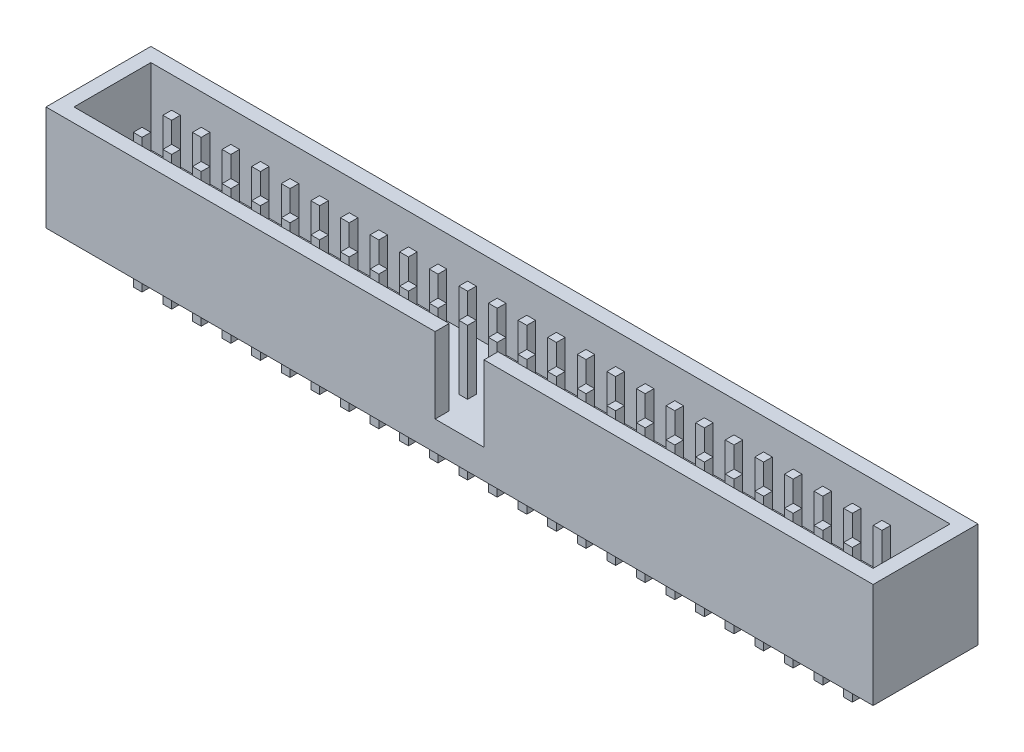
SolidWorks part; units mm, degrees
ref_plane "前视基准面" through (0, 0, 0) normal (0, 0, 1) x (1, 0, 0)
ref_plane "上视基准面" through (0, 0, 0) normal (0, 1, 0) x (1, 0, 0)
ref_plane "右视基准面" through (0, 0, 0) normal (1, 0, 0) x (0, 0, -1)
sketch "草图1" plane through (0, 0, 0) normal (0, 1, 0) x (1, 0, 0)
  line L0 (0, 85.0964) -> (0, -118.2031) construction
  line L1 (-35.49, 4.5) -> (35.49, 4.5)
  line L2 (-35.49, 4.5) -> (-35.49, -4.5)
  line L3 (-35.49, -4.5) -> (35.49, -4.5)
  line L4 (35.49, 4.5) -> (35.49, -4.5)
  line L5 (-200.5452, 0) -> (261.2352, 0) construction
  dimension "D1" = 9
  dimension "D2" = 70.98
extrude "拉伸1" add sketch "草图1" along normal blind 9
sketch "草图2" plane through (0, 9, 0) normal (0, 1, 0) x (-1, 0, 0)
  line L8 (-34.29, 3.3) -> (-34.29, -3.3)
  line L9 (34.29, 3.3) -> (-34.29, 3.3)
  line L10 (34.29, -3.3) -> (34.29, 3.3)
  line L11 (-34.29, -3.3) -> (34.29, -3.3)
  line L12 (-34.29, 3.3) -> (-34.29, -3.3)
  line L13 (34.29, 3.3) -> (-34.29, 3.3)
  line L14 (34.29, -3.3) -> (34.29, 3.3)
  line L15 (-34.29, -3.3) -> (34.29, -3.3)
  dimension "D1" = 1.2
extrude "切除-拉伸1" cut sketch "草图2" against normal blind 6.5
sketch "草图3" plane through (0, 0, 4.5) normal (0, 0, 1) x (1, 0, 0)
  line L0 (-35.49, 9) -> (35.49, 9) construction
  line L1 (-2.1, 9) -> (2.1, 9)
  line L2 (-2.1, 9) -> (-2.1, 2.5)
  line L3 (-2.1, 2.5) -> (2.1, 2.5)
  line L4 (2.1, 9) -> (2.1, 2.5)
  line L5 (-34.29, 2.5) -> (34.29, 2.5) construction
  line L6 (0, 9.4226) -> (0, -4.0288) construction
  dimension "D1" = 4.2
extrude "切除-拉伸2" cut sketch "草图3" against normal blind 6.5
sketch "草图6" plane through (0, 0, 0) normal (0, -1, 0) x (1, 0, 0)
  line L1 (2.1, 3.3) -> (34.29, 3.3) construction
  line L17 (30.85, 1.64) -> (30.1, 1.64)
  line L18 (30.1, 1.64) -> (30.1, 0.89)
  line L19 (30.1, 0.89) -> (30.85, 0.89)
  line L20 (30.85, 0.89) -> (30.85, 1.64)
  line L21 (34.29, 3.3) -> (34.29, -3.3) construction
  line L29 (28.31, 1.64) -> (27.56, 1.64)
  line L30 (27.56, 1.64) -> (27.56, 0.89)
  line L31 (27.56, 0.89) -> (28.31, 0.89)
  line L32 (28.31, 0.89) -> (28.31, 1.64)
  line L33 (25.77, 1.64) -> (25.02, 1.64)
  line L34 (25.02, 1.64) -> (25.02, 0.89)
  line L35 (25.02, 0.89) -> (25.77, 0.89)
  line L36 (25.77, 0.89) -> (25.77, 1.64)
  line L37 (23.23, 1.64) -> (22.48, 1.64)
  line L38 (22.48, 1.64) -> (22.48, 0.89)
  line L39 (22.48, 0.89) -> (23.23, 0.89)
  line L40 (23.23, 0.89) -> (23.23, 1.64)
  line L41 (20.69, 1.64) -> (19.94, 1.64)
  line L42 (19.94, 1.64) -> (19.94, 0.89)
  line L43 (19.94, 0.89) -> (20.69, 0.89)
  line L44 (20.69, 0.89) -> (20.69, 1.64)
  line L45 (18.15, 1.64) -> (17.4, 1.64)
  line L46 (17.4, 1.64) -> (17.4, 0.89)
  line L47 (17.4, 0.89) -> (18.15, 0.89)
  line L48 (18.15, 0.89) -> (18.15, 1.64)
  line L49 (15.61, 1.64) -> (14.86, 1.64)
  line L50 (14.86, 1.64) -> (14.86, 0.89)
  line L51 (14.86, 0.89) -> (15.61, 0.89)
  line L52 (15.61, 0.89) -> (15.61, 1.64)
  line L53 (13.07, 1.64) -> (12.32, 1.64)
  line L54 (12.32, 1.64) -> (12.32, 0.89)
  line L55 (12.32, 0.89) -> (13.07, 0.89)
  line L56 (13.07, 0.89) -> (13.07, 1.64)
  line L57 (10.53, 1.64) -> (9.78, 1.64)
  line L58 (9.78, 1.64) -> (9.78, 0.89)
  line L59 (9.78, 0.89) -> (10.53, 0.89)
  line L60 (10.53, 0.89) -> (10.53, 1.64)
  line L61 (7.99, 1.64) -> (7.24, 1.64)
  line L62 (7.24, 1.64) -> (7.24, 0.89)
  line L63 (7.24, 0.89) -> (7.99, 0.89)
  line L64 (7.99, 0.89) -> (7.99, 1.64)
  line L65 (5.45, 1.64) -> (4.7, 1.64)
  line L66 (4.7, 1.64) -> (4.7, 0.89)
  line L67 (4.7, 0.89) -> (5.45, 0.89)
  line L68 (5.45, 0.89) -> (5.45, 1.64)
  line L69 (2.91, 1.64) -> (2.16, 1.64)
  line L70 (2.16, 1.64) -> (2.16, 0.89)
  line L71 (2.16, 0.89) -> (2.91, 0.89)
  line L72 (2.91, 0.89) -> (2.91, 1.64)
  line L73 (0.37, 1.64) -> (-0.38, 1.64)
  line L74 (-0.38, 1.64) -> (-0.38, 0.89)
  line L75 (-0.38, 0.89) -> (0.37, 0.89)
  line L76 (0.37, 0.89) -> (0.37, 1.64)
  line L77 (-2.17, 1.64) -> (-2.92, 1.64)
  line L78 (-2.92, 1.64) -> (-2.92, 0.89)
  line L79 (-2.92, 0.89) -> (-2.17, 0.89)
  line L80 (-2.17, 0.89) -> (-2.17, 1.64)
  line L81 (-4.71, 1.64) -> (-5.46, 1.64)
  line L82 (-5.46, 1.64) -> (-5.46, 0.89)
  line L83 (-5.46, 0.89) -> (-4.71, 0.89)
  line L84 (-4.71, 0.89) -> (-4.71, 1.64)
  line L85 (-7.25, 1.64) -> (-8, 1.64)
  line L86 (-8, 1.64) -> (-8, 0.89)
  line L87 (-8, 0.89) -> (-7.25, 0.89)
  line L88 (-7.25, 0.89) -> (-7.25, 1.64)
  line L89 (-9.79, 1.64) -> (-10.54, 1.64)
  line L90 (-10.54, 1.64) -> (-10.54, 0.89)
  line L91 (-10.54, 0.89) -> (-9.79, 0.89)
  line L92 (-9.79, 0.89) -> (-9.79, 1.64)
  line L93 (-12.33, 1.64) -> (-13.08, 1.64)
  line L94 (-13.08, 1.64) -> (-13.08, 0.89)
  line L95 (-13.08, 0.89) -> (-12.33, 0.89)
  line L96 (-12.33, 0.89) -> (-12.33, 1.64)
  line L97 (-14.87, 1.64) -> (-15.62, 1.64)
  line L98 (-15.62, 1.64) -> (-15.62, 0.89)
  line L99 (-15.62, 0.89) -> (-14.87, 0.89)
  line L100 (-14.87, 0.89) -> (-14.87, 1.64)
  line L101 (-17.41, 1.64) -> (-18.16, 1.64)
  line L102 (-18.16, 1.64) -> (-18.16, 0.89)
  line L103 (-18.16, 0.89) -> (-17.41, 0.89)
  line L104 (-17.41, 0.89) -> (-17.41, 1.64)
  line L105 (-19.95, 1.64) -> (-20.7, 1.64)
  line L106 (-20.7, 1.64) -> (-20.7, 0.89)
  line L107 (-20.7, 0.89) -> (-19.95, 0.89)
  line L108 (-19.95, 0.89) -> (-19.95, 1.64)
  line L109 (-22.49, 1.64) -> (-23.24, 1.64)
  line L110 (-23.24, 1.64) -> (-23.24, 0.89)
  line L111 (-23.24, 0.89) -> (-22.49, 0.89)
  line L112 (-22.49, 0.89) -> (-22.49, 1.64)
  line L113 (-25.03, 1.64) -> (-25.78, 1.64)
  line L114 (-25.78, 1.64) -> (-25.78, 0.89)
  line L115 (-25.78, 0.89) -> (-25.03, 0.89)
  line L116 (-25.03, 0.89) -> (-25.03, 1.64)
  line L117 (-27.57, 1.64) -> (-28.32, 1.64)
  line L118 (-28.32, 1.64) -> (-28.32, 0.89)
  line L119 (-28.32, 0.89) -> (-27.57, 0.89)
  line L120 (-27.57, 0.89) -> (-27.57, 1.64)
  line L121 (-30.11, 1.64) -> (-30.86, 1.64)
  line L122 (-30.86, 1.64) -> (-30.86, 0.89)
  line L123 (-30.86, 0.89) -> (-30.11, 0.89)
  line L124 (-30.11, 0.89) -> (-30.11, 1.64)
  line L125 (28.31, -0.9) -> (27.56, -0.9)
  line L126 (27.56, -0.9) -> (27.56, -1.65)
  line L127 (27.56, -1.65) -> (28.31, -1.65)
  line L128 (28.31, -1.65) -> (28.31, -0.9)
  line L129 (25.77, -0.9) -> (25.02, -0.9)
  line L130 (25.02, -0.9) -> (25.02, -1.65)
  line L131 (25.02, -1.65) -> (25.77, -1.65)
  line L132 (25.77, -1.65) -> (25.77, -0.9)
  line L133 (23.23, -0.9) -> (22.48, -0.9)
  line L134 (22.48, -0.9) -> (22.48, -1.65)
  line L135 (22.48, -1.65) -> (23.23, -1.65)
  line L136 (23.23, -1.65) -> (23.23, -0.9)
  line L137 (20.69, -0.9) -> (19.94, -0.9)
  line L138 (19.94, -0.9) -> (19.94, -1.65)
  line L139 (19.94, -1.65) -> (20.69, -1.65)
  line L140 (20.69, -1.65) -> (20.69, -0.9)
  line L141 (18.15, -0.9) -> (17.4, -0.9)
  line L142 (17.4, -0.9) -> (17.4, -1.65)
  line L143 (17.4, -1.65) -> (18.15, -1.65)
  line L144 (18.15, -1.65) -> (18.15, -0.9)
  line L145 (15.61, -0.9) -> (14.86, -0.9)
  line L146 (14.86, -0.9) -> (14.86, -1.65)
  line L147 (14.86, -1.65) -> (15.61, -1.65)
  line L148 (15.61, -1.65) -> (15.61, -0.9)
  line L149 (13.07, -0.9) -> (12.32, -0.9)
  line L150 (12.32, -0.9) -> (12.32, -1.65)
  line L151 (12.32, -1.65) -> (13.07, -1.65)
  line L152 (13.07, -1.65) -> (13.07, -0.9)
  line L153 (10.53, -0.9) -> (9.78, -0.9)
  line L154 (9.78, -0.9) -> (9.78, -1.65)
  line L155 (9.78, -1.65) -> (10.53, -1.65)
  line L156 (10.53, -1.65) -> (10.53, -0.9)
  line L157 (7.99, -0.9) -> (7.24, -0.9)
  line L158 (7.24, -0.9) -> (7.24, -1.65)
  line L159 (7.24, -1.65) -> (7.99, -1.65)
  line L160 (7.99, -1.65) -> (7.99, -0.9)
  line L161 (5.45, -0.9) -> (4.7, -0.9)
  line L162 (4.7, -0.9) -> (4.7, -1.65)
  line L163 (4.7, -1.65) -> (5.45, -1.65)
  line L164 (5.45, -1.65) -> (5.45, -0.9)
  line L165 (2.91, -0.9) -> (2.16, -0.9)
  line L166 (2.16, -0.9) -> (2.16, -1.65)
  line L167 (2.16, -1.65) -> (2.91, -1.65)
  line L168 (2.91, -1.65) -> (2.91, -0.9)
  line L169 (0.37, -0.9) -> (-0.38, -0.9)
  line L170 (-0.38, -0.9) -> (-0.38, -1.65)
  line L171 (-0.38, -1.65) -> (0.37, -1.65)
  line L172 (0.37, -1.65) -> (0.37, -0.9)
  line L173 (-2.17, -0.9) -> (-2.92, -0.9)
  line L174 (-2.92, -0.9) -> (-2.92, -1.65)
  line L175 (-2.92, -1.65) -> (-2.17, -1.65)
  line L176 (-2.17, -1.65) -> (-2.17, -0.9)
  line L177 (-4.71, -0.9) -> (-5.46, -0.9)
  line L178 (-5.46, -0.9) -> (-5.46, -1.65)
  line L179 (-5.46, -1.65) -> (-4.71, -1.65)
  line L180 (-4.71, -1.65) -> (-4.71, -0.9)
  line L181 (-7.25, -0.9) -> (-8, -0.9)
  line L182 (-8, -0.9) -> (-8, -1.65)
  line L183 (-8, -1.65) -> (-7.25, -1.65)
  line L184 (-7.25, -1.65) -> (-7.25, -0.9)
  line L185 (-9.79, -0.9) -> (-10.54, -0.9)
  line L186 (-10.54, -0.9) -> (-10.54, -1.65)
  line L187 (-10.54, -1.65) -> (-9.79, -1.65)
  line L188 (-9.79, -1.65) -> (-9.79, -0.9)
  line L189 (-12.33, -0.9) -> (-13.08, -0.9)
  line L190 (-13.08, -0.9) -> (-13.08, -1.65)
  line L191 (-13.08, -1.65) -> (-12.33, -1.65)
  line L192 (-12.33, -1.65) -> (-12.33, -0.9)
  line L193 (-14.87, -0.9) -> (-15.62, -0.9)
  line L194 (-15.62, -0.9) -> (-15.62, -1.65)
  line L195 (-15.62, -1.65) -> (-14.87, -1.65)
  line L196 (-14.87, -1.65) -> (-14.87, -0.9)
  line L197 (-17.41, -0.9) -> (-18.16, -0.9)
  line L198 (-18.16, -0.9) -> (-18.16, -1.65)
  line L199 (-18.16, -1.65) -> (-17.41, -1.65)
  line L200 (-17.41, -1.65) -> (-17.41, -0.9)
  line L201 (-19.95, -0.9) -> (-20.7, -0.9)
  line L202 (-20.7, -0.9) -> (-20.7, -1.65)
  line L203 (-20.7, -1.65) -> (-19.95, -1.65)
  line L204 (-19.95, -1.65) -> (-19.95, -0.9)
  line L205 (-22.49, -0.9) -> (-23.24, -0.9)
  line L206 (-23.24, -0.9) -> (-23.24, -1.65)
  line L207 (-23.24, -1.65) -> (-22.49, -1.65)
  line L208 (-22.49, -1.65) -> (-22.49, -0.9)
  line L209 (-25.03, -0.9) -> (-25.78, -0.9)
  line L210 (-25.78, -0.9) -> (-25.78, -1.65)
  line L211 (-25.78, -1.65) -> (-25.03, -1.65)
  line L212 (-25.03, -1.65) -> (-25.03, -0.9)
  line L213 (-27.57, -0.9) -> (-28.32, -0.9)
  line L214 (-28.32, -0.9) -> (-28.32, -1.65)
  line L215 (-28.32, -1.65) -> (-27.57, -1.65)
  line L216 (-27.57, -1.65) -> (-27.57, -0.9)
  line L217 (-30.11, -0.9) -> (-30.86, -0.9)
  line L218 (-30.86, -0.9) -> (-30.86, -1.65)
  line L219 (-30.86, -1.65) -> (-30.11, -1.65)
  line L220 (-30.11, -1.65) -> (-30.11, -0.9)
  line L221 (30.85, -0.9) -> (30.1, -0.9)
  line L222 (30.1, -0.9) -> (30.1, -1.65)
  line L223 (30.1, -1.65) -> (30.85, -1.65)
  line L224 (30.85, -1.65) -> (30.85, -0.9)
  circle A0 centre (30.475, 1.265) radius 0.375 construction
  dimension "D1" = 0.75
  dimension "D2" = 1.66
  dimension "D3" = 3.44
  dimension "D4" = 25
  dimension "D5" = 2
extrude "凸台-拉伸1" add sketch "草图6" along normal blind 3.5 and the other way offset from surface (8 mm away) 1 other way up to face at (0, 9, 1.3)
